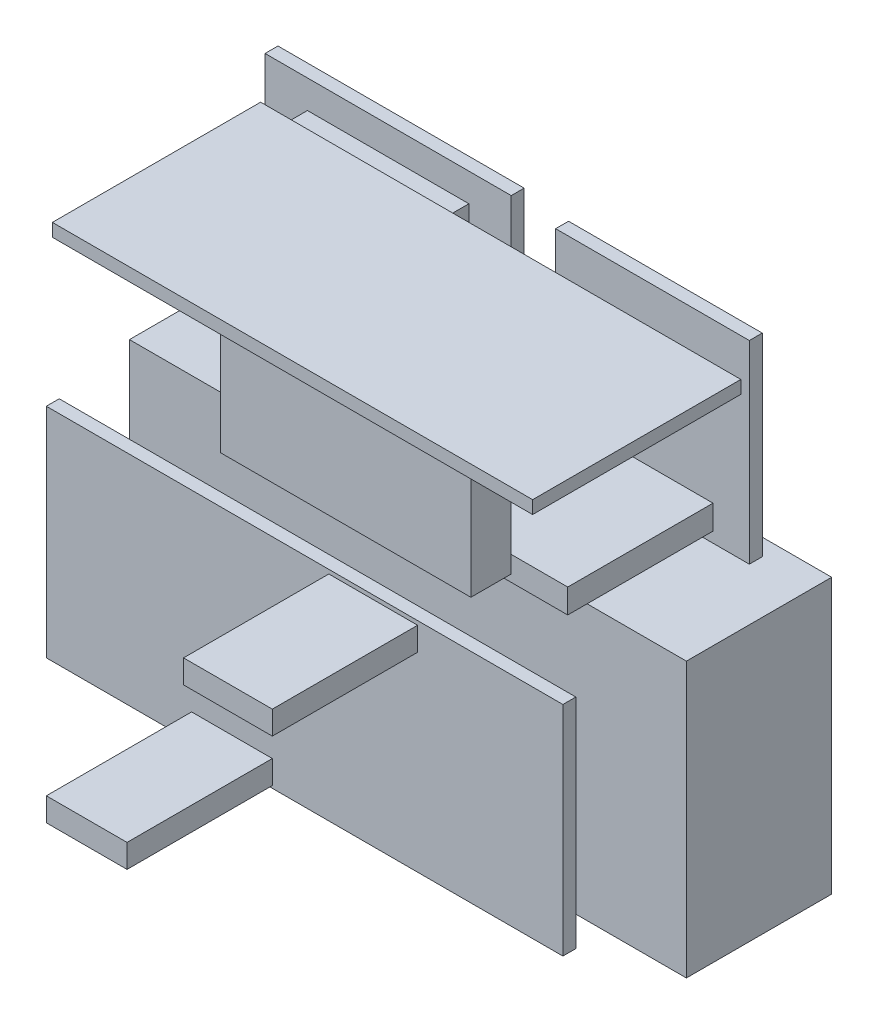
SolidWorks part; units mm, degrees
ref_plane "前视基准面" through (0, 0, 0) normal (0, 0, 1) x (1, 0, 0)
ref_plane "上视基准面" through (0, 0, 0) normal (0, 1, 0) x (1, 0, 0)
ref_plane "右视基准面" through (0, 0, 0) normal (1, 0, 0) x (0, 0, -1)
other "Configuration Table"
sketch "AA holder 69 x 34 x 18 profile" plane through (0, 0, 0) normal (0, 0, 1) x (1, 0, 0)
  line L0 (-35.5, -29) -> (33.5, -29)
  line L1 (33.5, -29) -> (33.5, 5)
  line L2 (33.5, 5) -> (-35.5, 5)
  line L3 (-35.5, 5) -> (-35.5, -29)
extrude "AA holder 69 x 34 x 18" add sketch "AA holder 69 x 34 x 18 profile" along normal blind 18 from offset 2.8 separate body
sketch "YBX board 24 x 24 profile" plane through (0, 0, 0) normal (0, 0, 1) x (1, 0, 0)
  line L0 (4.5, 6.5) -> (28.5, 6.5)
  line L1 (28.5, 6.5) -> (28.5, 30.5)
  line L2 (28.5, 30.5) -> (4.5, 30.5)
  line L3 (4.5, 30.5) -> (4.5, 6.5)
extrude "YBX board 24 x 24" add sketch "YBX board 24 x 24 profile" along normal blind 1.6 from offset 6.4 separate body
sketch "YBX jumper envelope profile" plane through (0, 0, 0) normal (0, 0, 1) x (1, 0, 0)
  line L0 (9, 7.8) -> (24, 7.8)
  line L1 (24, 7.8) -> (24, 10.8)
  line L2 (24, 10.8) -> (9, 10.8)
  line L3 (9, 10.8) -> (9, 7.8)
extrude "YBX jumper envelope" add sketch "YBX jumper envelope profile" along normal blind 18 from offset 8 separate body
sketch "GNSS board 30.5 x 25.5 profile" plane through (0, 0, 0) normal (0, 0, 1) x (1, 0, 0)
  line L0 (-31.5, 5.8) -> (-1, 5.8)
  line L1 (-1, 5.8) -> (-1, 31.3)
  line L2 (-1, 31.3) -> (-31.5, 31.3)
  line L3 (-31.5, 31.3) -> (-31.5, 5.8)
extrude "GNSS board 30.5 x 25.5" add sketch "GNSS board 30.5 x 25.5 profile" along normal blind 1.6 from offset 6.4 separate body
sketch "GNSS patch allowance only profile" plane through (0, 0, 0) normal (0, 0, 1) x (1, 0, 0)
  line L0 (-26.25, 11.8) -> (-6.25, 11.8)
  line L1 (-6.25, 11.8) -> (-6.25, 27.8)
  line L2 (-6.25, 27.8) -> (-26.25, 27.8)
  line L3 (-26.25, 27.8) -> (-26.25, 11.8)
extrude "GNSS patch allowance only" add sketch "GNSS patch allowance only profile" along normal blind 4 from offset 8 separate body
sketch "Power board 59.5 x 25.8 profile" plane through (0, 0, 0) normal (0, 0, 1) x (1, 0, 0)
  line L0 (-29.75, 26.5) -> (29.75, 26.5)
  line L1 (29.75, 26.5) -> (29.75, 28.1)
  line L2 (29.75, 28.1) -> (-29.75, 28.1)
  line L3 (-29.75, 28.1) -> (-29.75, 26.5)
extrude "Power board 59.5 x 25.8" add sketch "Power board 59.5 x 25.8 profile" along normal blind 25.8 from offset 10.3 separate body
sketch "Power horizontal connector envelope profile" plane through (0, 0, 0) normal (0, 0, 1) x (1, 0, 0)
  line L0 (-13, 9.7) -> (18, 9.7)
  line L1 (18, 9.7) -> (18, 26.5)
  line L2 (18, 26.5) -> (-13, 26.5)
  line L3 (-13, 26.5) -> (-13, 9.7)
extrude "Power horizontal connector envelope" add sketch "Power horizontal connector envelope profile" along normal blind 5 from offset 27 separate body
sketch "EoRa board 64 x 27 profile" plane through (0, 0, 0) normal (0, 0, 1) x (1, 0, 0)
  line L0 (-32, -20.5) -> (32, -20.5)
  line L1 (32, -20.5) -> (32, 6.5)
  line L2 (32, 6.5) -> (-32, 6.5)
  line L3 (-32, 6.5) -> (-32, -20.5)
extrude "EoRa board 64 x 27" add sketch "EoRa board 64 x 27 profile" along normal blind 1.6 from offset 33 separate body
sketch "EoRa upper connector envelope A profile" plane through (0, 0, 0) normal (0, 0, 1) x (1, 0, 0)
  line L0 (-14, -20.2) -> (-4, -20.2)
  line L1 (-4, -20.2) -> (-4, -17.3)
  line L2 (-4, -17.3) -> (-14, -17.3)
  line L3 (-14, -17.3) -> (-14, -20.2)
extrude "EoRa upper connector envelope A" add sketch "EoRa upper connector envelope A profile" along normal blind 18 from offset 34.6 separate body
sketch "EoRa upper connector envelope B profile" plane through (0, 0, 0) normal (0, 0, 1) x (1, 0, 0)
  line L0 (3, 3.1) -> (14, 3.1)
  line L1 (14, 3.1) -> (14, 6)
  line L2 (14, 6) -> (3, 6)
  line L3 (3, 6) -> (3, 3.1)
extrude "EoRa upper connector envelope B" add sketch "EoRa upper connector envelope B profile" along normal blind 18 from offset 34.6 separate body
